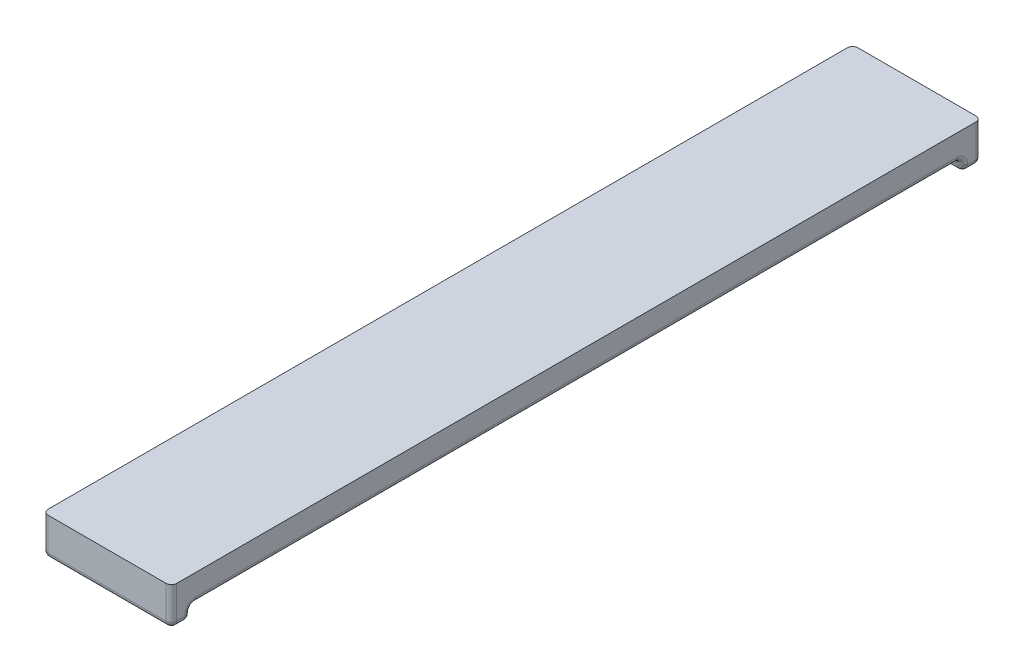
SolidWorks part; units mm, degrees
ref_plane "Front Plane" through (0, 0, 0) normal (0, 0, 1) x (1, 0, 0)
ref_plane "Top Plane" through (0, 0, 0) normal (0, 1, 0) x (1, 0, 0)
ref_plane "Right Plane" through (0, 0, 0) normal (1, 0, 0) x (0, 0, -1)
sketch "Sketch1" plane through (0, 0, 0) normal (0, 1, 0) x (1, 0, 0)
  line L0 (-17.6031, -25.4) -> (-9.1435, -25.4) construction
  line L1 (-17.6031, -25.4) -> (-17.6031, 25.4)
  line L2 (-17.6031, 25.4) -> (-9.1435, 25.4) construction
  line L3 (-9.1435, -25.4) -> (-9.1435, 25.4)
  line L4 (-17.6031, -25.4) -> (-9.1435, 25.4) construction
  line L5 (-17.6031, 25.4) -> (-9.1435, -25.4) construction
  line L6 (-1.375, 0) -> (1.375, 0) construction
  line L7 (-17.6031, -25.4) -> (-9.1435, -25.4) construction
  line L8 (-17.6031, -25.4) -> (-17.6031, -26.65)
  line L9 (-17.6031, -26.65) -> (-9.1435, -26.65)
  line L10 (-9.1435, -25.4) -> (-9.1435, -26.65)
  line L11 (-17.6031, -25.4) -> (-9.1435, -26.65) construction
  line L12 (-17.6031, -26.65) -> (-9.1435, -25.4) construction
  line L13 (-17.6031, 25.4) -> (-9.1435, 26.65) construction
  line L14 (-17.6031, 26.65) -> (-9.1435, 25.4) construction
  line L15 (-9.1435, 25.4) -> (-9.1435, 26.65)
  line L16 (-17.6031, 26.65) -> (-9.1435, 26.65)
  line L17 (-17.6031, 25.4) -> (-17.6031, 26.65)
  point P4 (-13.3733, 0)
  point P7 (-13.3733, -26.025)
  dimension "D1" = 8.4596
  dimension "D2" = 50.8
  dimension "D3" = 1.25
extrude "Boss-Extrude1" add sketch "Sketch1" along normal blind 1.75
sketch "Sketch2" plane through (0, 0, 0) normal (0, -1, 0) x (1, 0, 0)
  line L0 (-17.6031, -25.4) -> (-9.1435, -26.65) construction
  line L1 (-17.6031, 25.4) -> (-9.1435, 25.4)
  line L2 (-17.6031, 25.4) -> (-17.6031, 26.65)
  line L3 (-17.6031, 26.65) -> (-9.1435, 26.65)
  line L4 (-9.1435, 25.4) -> (-9.1435, 26.65)
  line L5 (-17.6031, 25.4) -> (-9.1435, 26.65) construction
  line L6 (-17.6031, 26.65) -> (-9.1435, 25.4) construction
  line L7 (-17.6031, -25.4) -> (-9.1435, -25.4)
  line L8 (-17.6031, -25.4) -> (-17.6031, -26.65)
  line L9 (-17.6031, -26.65) -> (-9.1435, -26.65)
  line L10 (-9.1435, -25.4) -> (-9.1435, -26.65)
  line L11 (-17.6031, -25.4) -> (-9.1435, -26.65) construction
  line L12 (-17.6031, -26.65) -> (-9.1435, -25.4) construction
  point P0 (-13.3733, 26.025)
  point P7 (-13.3733, -26.025)
extrude "Boss-Extrude2" add sketch "Sketch2" along normal blind 0.75
sketch "Sketch3" plane through (0, 0, 0) normal (0, -1, 0) x (1, 0, 0)
  line L0 (-17.6031, 25.4) -> (-17.6031, -25.4) construction
  line L1 (-17.6031, -24.3) -> (-12.1031, -24.3)
  line L2 (-17.6031, -24.3) -> (-17.6031, -21.3)
  line L3 (-17.6031, -21.3) -> (-12.1031, -21.3)
  line L4 (-12.1031, -24.3) -> (-12.1031, -21.3) construction
  line L5 (-17.6031, -24.3) -> (-12.1031, -21.3) construction
  line L6 (-17.6031, -21.3) -> (-12.1031, -24.3) construction
  line L7 (-17.6031, -25.4) -> (-9.1435, -25.4) construction
  arc A0 (-12.1031, -24.3) -> (-12.1031, -21.3) centre (-12.1031, -22.8) ccw
  point P4 (-14.8531, -22.8)
  dimension "D1" = 1.1
  dimension "D2" = 3
  dimension "D3" = 5.5
extrude "Boss-Extrude3" add sketch "Sketch3" along normal blind 1.25
pattern_linear "LPattern1" count 10 spacing 5.068 along (0, 0, 1) of "Boss-Extrude3"
fillet "Fillet1" radius 0.35 120 edges at (-17.6031, -0.625, 24.312) (-17.6031, -0.375, 25.4) (-9.1435, -0.375, 25.4) (-9.1435, -0.375, -25.4) (-17.6031, -0.375, -25.4) (-17.6031, -0.625, -24.3) (-17.6031, -0.625, -21.3) (-17.6031, -0.625, -19.232) (-17.6031, -0.625, -16.232) (-17.6031, -0.625, -14.164) (-17.6031, -0.625, -11.164) (-17.6031, -0.625, -9.096) (-17.6031, -0.625, -6.096) (-17.6031, -0.625, -4.028) (-17.6031, -0.625, -1.028) (-17.6031, -0.625, 1.04) (-17.6031, -0.625, 4.04) (-17.6031, -0.625, 6.108) (-17.6031, -0.625, 9.108) (-17.6031, -0.625, 11.176) (-17.6031, -0.625, 14.176) (-17.6031, -0.625, 16.244) (-17.6031, -0.625, 19.244) (-17.6031, -0.625, 21.312) (-14.8531, -1.25, -24.3) (-14.8531, -1.25, -21.3) (-13.3733, -0.75, 25.4) (-17.6031, -0.75, 26.025) (-13.3733, -0.75, 26.65) (-9.1435, -0.75, 26.025) (-14.8531, -1.25, -16.232) (-10.6031, -1.25, -17.732) (-14.8531, -1.25, -19.232) (-17.6031, -1.25, -17.732) (-10.6031, 0, 22.812) (-14.8531, 0, 24.312) (-17.6031, 0, 24.856) (-13.3733, 0, 25.4) (-9.1435, 0, 0) (-13.3733, 0, -25.4) (-17.6031, 0, -24.85) (-14.8531, 0, -24.3) (-10.6031, 0, -22.8) (-14.8531, 0, -21.3) (-17.6031, 0, -20.266) (-14.8531, 0, -19.232) (-10.6031, 0, -17.732) (-14.8531, 0, -16.232) (-17.6031, 0, -15.198) (-14.8531, 0, -14.164) (-10.6031, 0, -12.664) (-14.8531, 0, -11.164) (-17.6031, 0, -10.13) (-14.8531, 0, -9.096) (-10.6031, 0, -7.596) (-14.8531, 0, -6.096) (-17.6031, 0, -5.062) (-14.8531, 0, -4.028) (-10.6031, 0, -2.528) (-14.8531, 0, -1.028) (-17.6031, 0, 0.006) (-14.8531, 0, 1.04) (-10.6031, 0, 2.54) (-14.8531, 0, 4.04) (-17.6031, 0, 5.074) (-14.8531, 0, 6.108) (-10.6031, 0, 7.608) (-14.8531, 0, 9.108) (-17.6031, 0, 10.142) (-14.8531, 0, 11.176) (-10.6031, 0, 12.676) (-14.8531, 0, 14.176) (-17.6031, 0, 15.21) (-14.8531, 0, 16.244) (-10.6031, 0, 17.744) (-14.8531, 0, 19.244) (-17.6031, 0, 20.278) (-14.8531, 0, 21.312) (-14.8531, -1.25, 19.244) (-10.6031, -1.25, 17.744) (-14.8531, -1.25, 16.244) (-17.6031, -1.25, 17.744) (-14.8531, -1.25, 24.312) (-10.6031, -1.25, 22.812) (-14.8531, -1.25, 21.312) (-17.6031, -1.25, 22.812) (-13.3733, -0.75, -26.65) (-17.6031, -0.75, -26.025) (-13.3733, -0.75, -25.4) (-9.1435, -0.75, -26.025) (-14.8531, -1.25, -11.164) (-10.6031, -1.25, -12.664) (-14.8531, -1.25, -14.164) (-17.6031, -1.25, -12.664) (-14.8531, -1.25, -6.096) (-10.6031, -1.25, -7.596) (-14.8531, -1.25, -9.096) (-17.6031, -1.25, -7.596) (-14.8531, -1.25, -1.028) (-10.6031, -1.25, -2.528) (-14.8531, -1.25, -4.028) (-17.6031, -1.25, -2.528) (-14.8531, -1.25, 4.04) (-10.6031, -1.25, 2.54) (-14.8531, -1.25, 1.04) (-17.6031, -1.25, 2.54) (-14.8531, -1.25, 9.108) (-10.6031, -1.25, 7.608) (-14.8531, -1.25, 6.108) (-17.6031, -1.25, 7.608) (-14.8531, -1.25, 14.176) (-10.6031, -1.25, 12.676) (-14.8531, -1.25, 11.176) (-17.6031, -1.25, 12.676) (-17.6031, 0.5, -26.65) (-9.1435, 0.5, -26.65) (-17.6031, 0.5, 26.65) (-9.1435, 0.5, 26.65) (-17.6031, -1.25, -22.8) (-10.6031, -1.25, -22.8)
